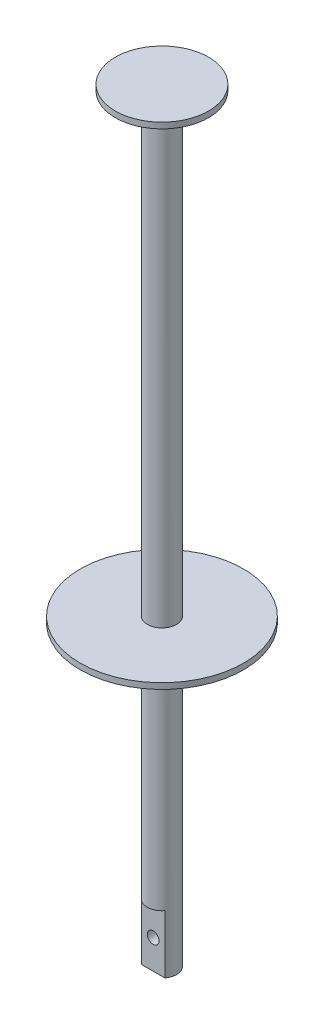
SolidWorks part; units mm, degrees
ref_plane "前视基准面" through (0, 0, 0) normal (0, 0, 1) x (1, 0, 0)
ref_plane "上视基准面" through (0, 0, 0) normal (0, 1, 0) x (1, 0, 0)
ref_plane "右视基准面" through (0, 0, 0) normal (1, 0, 0) x (0, 0, -1)
sketch "草图1" plane through (0, 0, 0) normal (0, 1, 0) x (1, 0, 0)
  circle A0 centre (0, 0) radius 8
  dimension "D1" = 16
extrude "凸台-拉伸1" add sketch "草图1" along normal blind 1
sketch "草图3" plane through (0, 0, 0) normal (0, -1, 0) x (1, 0, 0)
  circle A0 centre (0, 0) radius 2.5
  dimension "D1" = 5
extrude "凸台-拉伸2" add sketch "草图3" along normal blind 130
ref_plane "基准面2" through (2.5, 0, 0) normal (1, 0, 0) x (0, 0, -1)
sketch "草图5" plane through (2.5, 0, 0) normal (1, 0, 0) x (0, 0, -1)
  line L0 (-2.5, -130) -> (-1.5, -130)
  line L1 (-2.5, -130) -> (2.5, -130) construction
  line L2 (-1.5, -130) -> (-1.5, -120)
  line L3 (-1.5, -120) -> (-2.5, -120)
  line L4 (-2.5, 0) -> (-2.5, -130) construction
  line L5 (-2.5, -120) -> (-2.5, -130)
  line L6 (0, -130) -> (0, -120) construction
  line L7 (1.5, -120) -> (2.5, -120)
  line L8 (1.5, -130) -> (1.5, -120)
  line L9 (2.5, -130) -> (1.5, -130)
  line L10 (2.5, -120) -> (2.5, -130)
  dimension "D1" = 1
  dimension "D2" = 10
extrude "切除-拉伸1" cut sketch "草图5" against normal through all
sketch "草图6" plane through (0, 0, 1.5) normal (0, 0, 1) x (1, 0, 0)
  line L0 (0, -120) -> (0, -130) construction
  line L1 (-2, -120) -> (2, -120) construction
  line L2 (-2, -130) -> (2, -130) construction
  circle A0 centre (0, -125) radius 1
  dimension "D1" = 2
extrude "切除-拉伸2" cut sketch "草图6" against normal through all
ref_plane "基准面3" through (0, -79, 0) normal (0, 1, 0) x (1, 0, 0)
sketch "草图8" plane through (0, -79, 0) normal (0, 1, 0) x (1, 0, 0)
  circle A0 centre (0, 0) radius 14
  dimension "D1" = 28
extrude "凸台-拉伸3" add sketch "草图8" along normal blind 1
